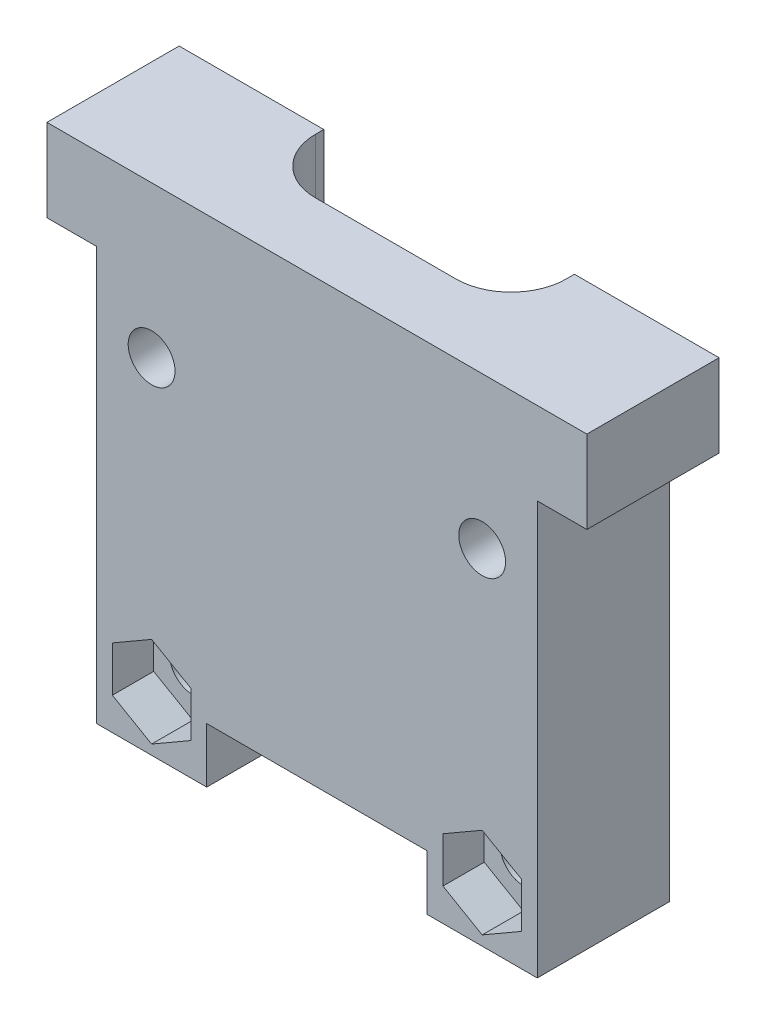
SolidWorks part; units mm, degrees
ref_plane "Спереди" through (0, 0, 0) normal (0, 0, 1) x (1, 0, 0)
ref_plane "Сверху" through (0, 0, 0) normal (0, 1, 0) x (1, 0, 0)
ref_plane "Справа" through (0, 0, 0) normal (1, 0, 0) x (0, 0, -1)
sketch "Эскиз1" plane through (0, 0, 0) normal (0, 0, 1) x (1, 0, 0)
  line L0 (0, 16) -> (0, -16) construction
  line L1 (8, -16) -> (-8, -16)
  line L2 (16, -16) -> (16, 16)
  line L3 (16, 16) -> (-16, 16)
  line L4 (-16, -16) -> (-16, 16)
  line L5 (16, -16) -> (-16, 16) construction
  line L6 (16, 16) -> (-16, -16) construction
  line L7 (-8, -16) -> (-8, -20)
  line L8 (16, -16) -> (16, -20)
  line L9 (16, -20) -> (8, -20)
  line L10 (8, -16) -> (8, -20)
  line L11 (-16, -20) -> (-8, -20)
  line L12 (-16, -16) -> (-16, -20)
  point P0 (0, 0)
  dimension "D1" = 32
  dimension "D2" = 32
  dimension "D3" = 8
  dimension "D4" = 4
extrude "Бобышка-Вытянуть1" add sketch "Эскиз1" along normal blind 16
sketch "Эскиз2" plane through (0, 16, 0) normal (0, 1, 0) x (1, 0, 0)
  line L1 (5.1, -11) -> (-5.1, -11)
  line L2 (9.1, -7) -> (9.1, -5.8)
  line L3 (5.1, -1.8) -> (-5.1, -1.8)
  line L4 (-9.1, -7) -> (-9.1, -5.8)
  line L5 (9.1, -11) -> (-9.1, -1.8) construction
  line L6 (9.1, -1.8) -> (-9.1, -11) construction
  line L7 (16, -16) -> (-16, -16) construction
  arc A0 (5.1, -1.8) -> (9.1, -5.8) centre (5.1, -5.8) cw
  arc A1 (9.1, -7) -> (5.1, -11) centre (5.1, -7) cw
  arc A2 (-5.1, -11) -> (-9.1, -7) centre (-5.1, -7) cw
  arc A3 (-9.1, -5.8) -> (-5.1, -1.8) centre (-5.1, -5.8) cw
  point P0 (0, -6.4)
  dimension "D4" = 4
  dimension "D1" = 9.2
  dimension "D2" = 5
  dimension "D3" = 18.2
extrude "Вырез-Вытянуть1" cut sketch "Эскиз2" against normal blind 29
fillet "Скругление1" radius 3 8 edges at (9.1, -13, 6.4) (7.9284, -13, 9.8284) (0, -13, 11) (-7.9284, -13, 9.8284) (-9.1, -13, 6.4) (-7.9284, -13, 2.9716) (0, -13, 1.8) (7.9284, -13, 2.9716)
sketch "Эскиз3" plane through (0, 0, 0) normal (0, 0, -1) x (-1, 0, 0)
  line L0 (0, 16) -> (0, -16) construction
  line L1 (-16, 16) -> (16, 16) construction
  line L2 (8, -16) -> (-8, -16) construction
  line L5 (-16, 16) -> (16, 16) construction
  circle A0 centre (-12, -16) radius 1.7
  circle A1 centre (-12, 5) radius 1.7
  circle A2 centre (12, 5) radius 1.7
  circle A3 centre (12, -16) radius 1.7
  dimension "D1" = 3.4
  dimension "D4" = 11
  dimension "D5" = 3.4
  dimension "D2" = 12
  dimension "D3" = 32
extrude "Вырез-Вытянуть2" cut sketch "Эскиз3" against normal up to surface (16 mm away) up to face at (0, -10, 16)
sketch "Эскиз4" plane through (0, -16, 0) normal (0, 1, 0) x (1, 0, 0)
  line L0 (-6.1, -5.8) -> (-6.1, -7) construction
  circle A0 centre (0, -6.4) radius 2.2
  point P6 (-6.1, -6.4)
  dimension "D1" = 4.4
extrude "Вырез-Вытянуть3" cut sketch "Эскиз4" along normal up to surface (32 mm away)
sketch "Эскиз5" plane through (0, 0, 16) normal (0, 0, 1) x (1, 0, 0)
  line L0 (0, -16) -> (0, 0) construction
  line L1 (-12, -12.7091) -> (-14.85, -14.3546)
  line L2 (-14.85, -14.3546) -> (-14.85, -17.6454)
  line L3 (-14.85, -17.6454) -> (-12, -19.2909)
  line L4 (-12, -19.2909) -> (-9.15, -17.6454)
  line L5 (-9.15, -17.6454) -> (-9.15, -14.3546)
  line L6 (-9.15, -14.3546) -> (-12, -12.7091)
  line L7 (-8, -16) -> (8, -16) construction
  line L8 (9.15, -14.3546) -> (12, -12.7091)
  line L9 (9.15, -17.6454) -> (9.15, -14.3546)
  line L10 (12, -19.2909) -> (9.15, -17.6454)
  line L11 (14.85, -17.6454) -> (12, -19.2909)
  line L12 (14.85, -14.3546) -> (14.85, -17.6454)
  line L13 (12, -12.7091) -> (14.85, -14.3546)
  circle A0 centre (-12, -16) radius 2.85 construction
  circle A1 centre (12, -16) radius 2.85 construction
  dimension "D1" = 5.7
extrude "Вырез-Вытянуть4" cut sketch "Эскиз5" against normal blind 3
sketch "Эскиз6" plane through (0, 0, 0) normal (0, 0, -1) x (-1, 0, 0)
  line L0 (0, 0) -> (0, -16) construction
  line L1 (-16, -20) -> (-8, -20)
  line L2 (-16, -20) -> (-16, -12)
  line L3 (-16, -12) -> (-8, -12)
  line L4 (-8, -20) -> (-8, -12)
  line L5 (8, -16) -> (-8, -16) construction
  line L6 (-8, -16) -> (-8, -20) construction
  line L7 (8, -20) -> (8, -12)
  line L8 (16, -12) -> (8, -12)
  line L9 (16, -20) -> (16, -12)
  line L10 (16, -20) -> (8, -20)
  circle A0 centre (-12, -16) radius 1.7
  circle A1 centre (-12, -16) radius 1.7 construction
  circle A2 centre (12, -16) radius 1.7
extrude "Бобышка-Вытянуть2" add sketch "Эскиз6" along normal blind 13
sketch "Эскиз8" plane through (0, 16, 0) normal (0, 1, 0) x (1, 0, 0)
  line L2 (19.6, -16) -> (-19.6, -16)
  line L3 (19.6, -16) -> (19.6, 3.2)
  line L4 (19.6, 3.2) -> (-19.6, 3.2)
  line L5 (-19.6, -16) -> (-19.6, 3.2)
  line L6 (19.6, -16) -> (-19.6, 3.2) construction
  line L7 (19.6, 3.2) -> (-19.6, -16) construction
  line L19 (-9.1, -5.8) -> (-9.1, -7)
  line L20 (-5.1, -11) -> (5.1, -11)
  line L21 (9.1, -7) -> (9.1, -5.8)
  line L22 (5.1, -1.8) -> (-5.1, -1.8)
  line L23 (-9.1, -5.8) -> (-9.1, -7)
  line L24 (-5.1, -11) -> (5.1, -11)
  line L25 (9.1, -7) -> (9.1, -5.8)
  line L26 (5.1, -1.8) -> (-5.1, -1.8)
  arc A13 (-9.1, -7) -> (-5.1, -11) centre (-5.1, -7) ccw
  arc A14 (9.1, -5.8) -> (5.1, -1.8) centre (5.1, -5.8) ccw
  arc A15 (5.1, -11) -> (9.1, -7) centre (5.1, -7) ccw
  arc A16 (-5.1, -1.8) -> (-9.1, -5.8) centre (-5.1, -5.8) ccw
  arc A17 (-9.1, -7) -> (-5.1, -11) centre (-5.1, -7) ccw
  arc A18 (9.1, -5.8) -> (5.1, -1.8) centre (5.1, -5.8) ccw
  arc A19 (5.1, -11) -> (9.1, -7) centre (5.1, -7) ccw
  arc A20 (-5.1, -1.8) -> (-9.1, -5.8) centre (-5.1, -5.8) ccw
  point P5 (0, -6.4)
  dimension "D1" = 19.2
  dimension "D2" = 39.2
  dimension "D3" = 0
extrude "Бобышка-Вытянуть3" add sketch "Эскиз8" against normal blind 6
sketch "Эскиз9" plane through (0, 16, 0) normal (0, 1, 0) x (1, 0, 0)
  line L0 (-19.6, 3.2) -> (-19.6, -16) construction
  line L1 (-19.6, -6.4) -> (22.1796, -6.4)
  line L2 (-19.6, -6.4) -> (-19.6, 15.7317)
  line L3 (-19.6, 15.7317) -> (22.1796, 15.7317)
  line L4 (22.1796, -6.4) -> (22.1796, 15.7317)
extrude "Вырез-Вытянуть5" cut sketch "Эскиз9" against normal through all
